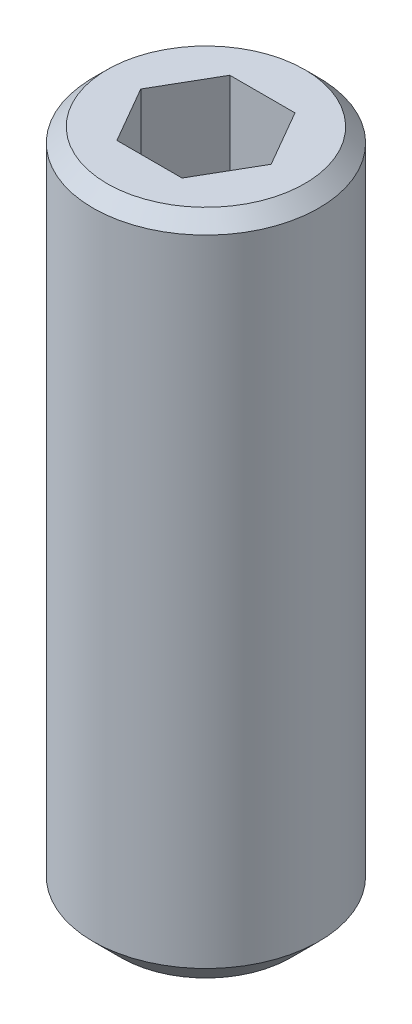
SolidWorks part; units mm, degrees
material "Alloy Steel"
ref_plane "Front Plane" through (0, 0, 0) normal (0, 0, 1) x (1, 0, 0)
ref_plane "Top Plane" through (0, 0, 0) normal (0, 1, 0) x (1, 0, 0)
ref_plane "Right Plane" through (0, 0, 0) normal (1, 0, 0) x (0, 0, -1)
sketch "Sketch1" plane through (0, 0, 0) normal (0, 1, 0) x (1, 0, 0)
  circle A0 centre (0, 0) radius 2
  dimension "D1" = 4
extrude "Extrude1" add sketch "Sketch1" along normal blind 12
chamfer "Chamfer1" distance 0.25 angle 45 1 edges at (0, 12, 2)
chamfer "Chamfer2" distance 0.5 angle 45 1 edges at (0, 0, 2)
sketch "Sketch2" plane through (0, 12, 0) normal (0, 1, 0) x (1, 0, 0)
  line L1 (-1.1547, 0) -> (-0.5774, -1)
  line L2 (-0.5774, -1) -> (0.5774, -1)
  line L3 (0.5774, -1) -> (1.1547, 0)
  line L4 (1.1547, 0) -> (0.5774, 1)
  line L5 (0.5774, 1) -> (-0.5774, 1)
  line L6 (-0.5774, 1) -> (-1.1547, 0)
  circle A0 centre (0, 0) radius 1 construction
  dimension "D1" = 2
extrude "Extrude2" cut sketch "Sketch2" against normal blind 1.5
